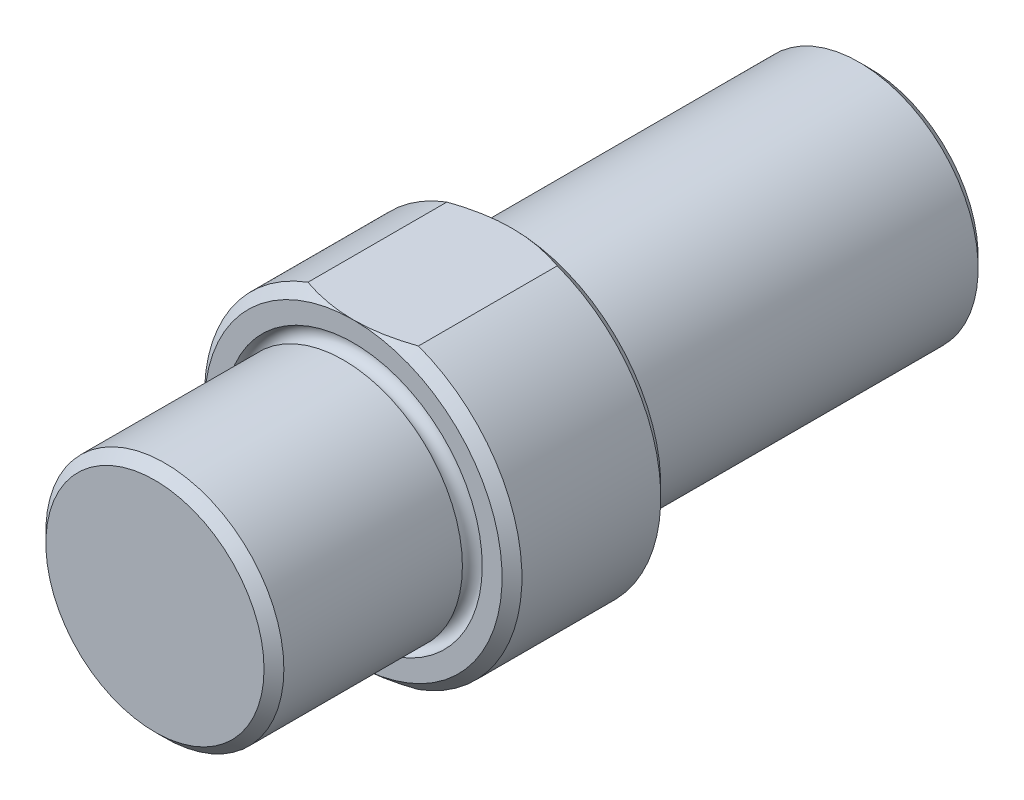
SolidWorks part; units mm, degrees
material "6061-T6 (AL)"
ref_plane "Front Plane" through (0, 0, 0) normal (0, 0, 1) x (1, 0, 0)
ref_plane "Top Plane" through (0, 0, 0) normal (0, 1, 0) x (1, 0, 0)
ref_plane "Right Plane" through (0, 0, 0) normal (1, 0, 0) x (0, 0, -1)
sketch "Sketch1" plane through (0, 0, 0) normal (1, 0, 0) x (0, 0, -1)
  line L0 (-4, 4) -> (0, 4)
  line L1 (0, 4) -> (0, 3)
  line L2 (0, 3) -> (9, 3)
  line L3 (9, 3) -> (9, 0)
  line L4 (9, 0) -> (-9, 0)
  line L5 (-9, 0) -> (-9, 3)
  line L6 (-9, 3) -> (-4, 3)
  line L7 (-4, 3) -> (-4, 4)
  dimension "D1" = 9
  dimension "D2" = 3
  dimension "D3" = 5
  dimension "D4" = 4
  dimension "D5" = 4
revolve "Revolve1" add sketch "Sketch1" angle 360 about L4
cosmetic thread "Cosmetic Thread1" parameters "D2"=4.891
hole_wizard "M4x0.7 Tapped Hole1" positions "Sketch2" profile "Sketch4" tap size "M4x0.7" standard "ANSI Metric"
sketch "Sketch2" plane through (0, 0, -9) normal (0, 0, -1) x (-1, 0, 0)
  point P0 (0, 0)
sketch "Sketch4" plane through (0, 0, -9) normal (1, 0, 0) x (0, 1, 0)
  line L0 (0, 0) -> (0, 10.9914)
  line L1 (0, 10.9914) -> (1.65, 10)
  line L2 (1.65, 10) -> (1.65, 0)
  line L5 (1.65, 0) -> (0, 0)
  line L10 (0, 10.9914) -> (-1.65, 10) construction
  line L11 (0, -6.35) -> (0, 107.95) construction
  dimension "Tap Drill Dia." = 3.3
  dimension "Tap Drill Depth" = 10
  dimension "Drill Angle" = 118
cosmetic thread "Hole Thread1" parameters "D1"=10, "D2"=4
sketch "Sketch5" plane through (0, 0, 0) normal (1, 0, 0) x (0, 0, -1)
  line L0 (-9, 0) -> (9, 0) construction
  line L1 (-9, 3) -> (-9, -3) construction
  line L2 (9, -3) -> (9, 3) construction
  circle A0 centre (-4, 3) radius 0.25
  circle A1 centre (0, 3) radius 0.25
  dimension "D1" = 0.5
revolve "Cut-Revolve1" cut sketch "Sketch5" angle 360 about L0
chamfer "Chamfer1" distance 0.25 angle 45 4 edges at (-4, 0, 0) (-4, 0, 4) (-3, 0, 9) (-3, 0, -9)
sketch "Sketch6" plane through (0, 0, 0) normal (0, 0, -1) x (-1, 0, 0)
  line L0 (-1.3919, 3.75) -> (1.3919, 3.75)
  line L1 (-1.3919, -3.75) -> (1.3919, -3.75)
  circle A2 centre (0, 0) radius 4 construction
  circle A3 centre (0, 0) radius 4
  circle A4 centre (0, 0) radius 3.75 construction
  point P3 (0, 3.75)
  point P6 (0, -3.75)
  point P9 (-1.5013, 3.7076)
  point P10 (1.4647, 3.7222)
  point P11 (0, 3.75)
  point P14 (-1.3919, -3.75)
  point P15 (1.5493, -3.6878)
  point P16 (0, -3.75)
extrude "Cut-Extrude1" cut sketch "Sketch6" against normal up to next contours L0 A3 | L1 A3
